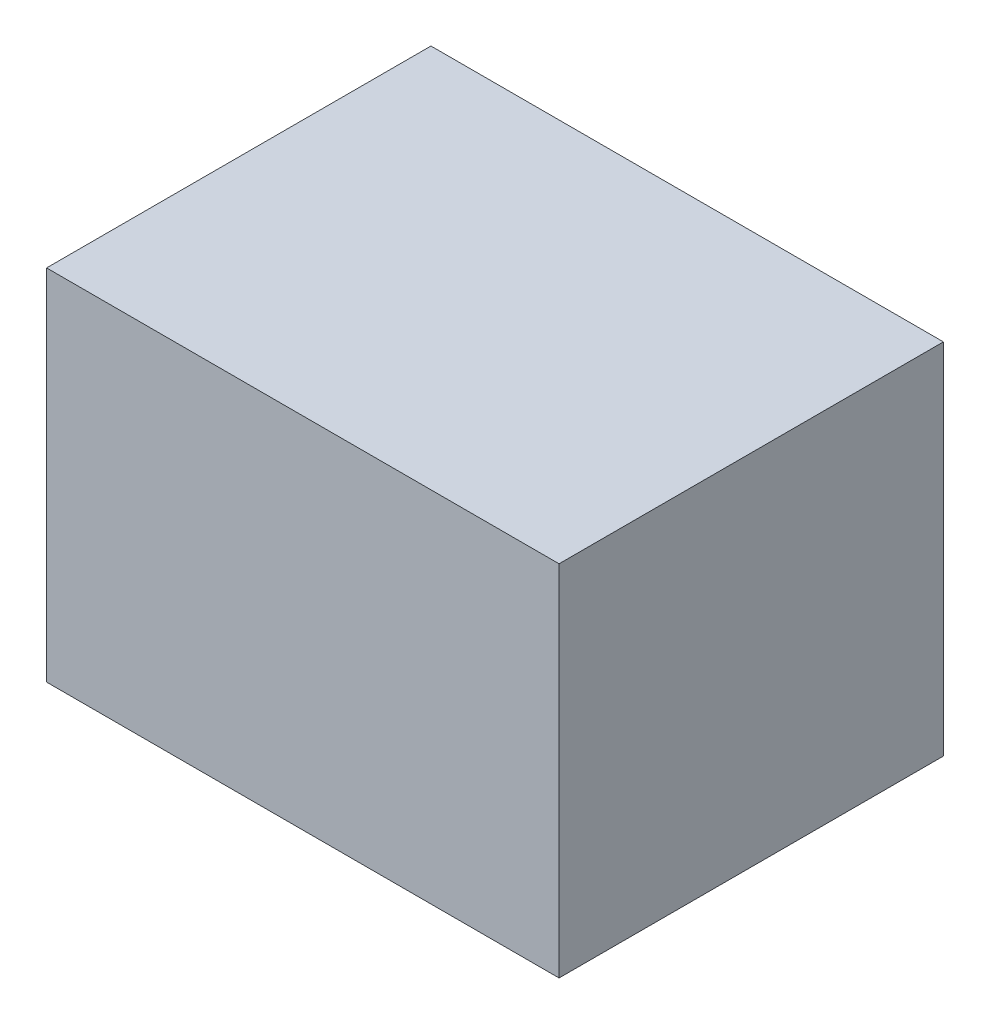
SolidWorks part; units mm, degrees
ref_plane "Front Plane" through (0, 0, 0) normal (0, 0, 1) x (1, 0, 0)
ref_plane "Top Plane" through (0, 0, 0) normal (0, 1, 0) x (1, 0, 0)
ref_plane "Right Plane" through (0, 0, 0) normal (1, 0, 0) x (0, 0, -1)
sketch "Sketch1" plane through (0, 0, 0) normal (0, 0, 1) x (1, 0, 0)
  line L1 (-10, -7) -> (10, -7)
  line L2 (-10, -7) -> (-10, 7)
  line L3 (-10, 7) -> (10, 7)
  line L4 (10, -7) -> (10, 7)
  line L5 (-10, -7) -> (10, 7) construction
  line L6 (-10, 7) -> (10, -7) construction
  point P0 (0, 0)
extrude "Boss-Extrude1" add sketch "Sketch1" against normal blind 15
